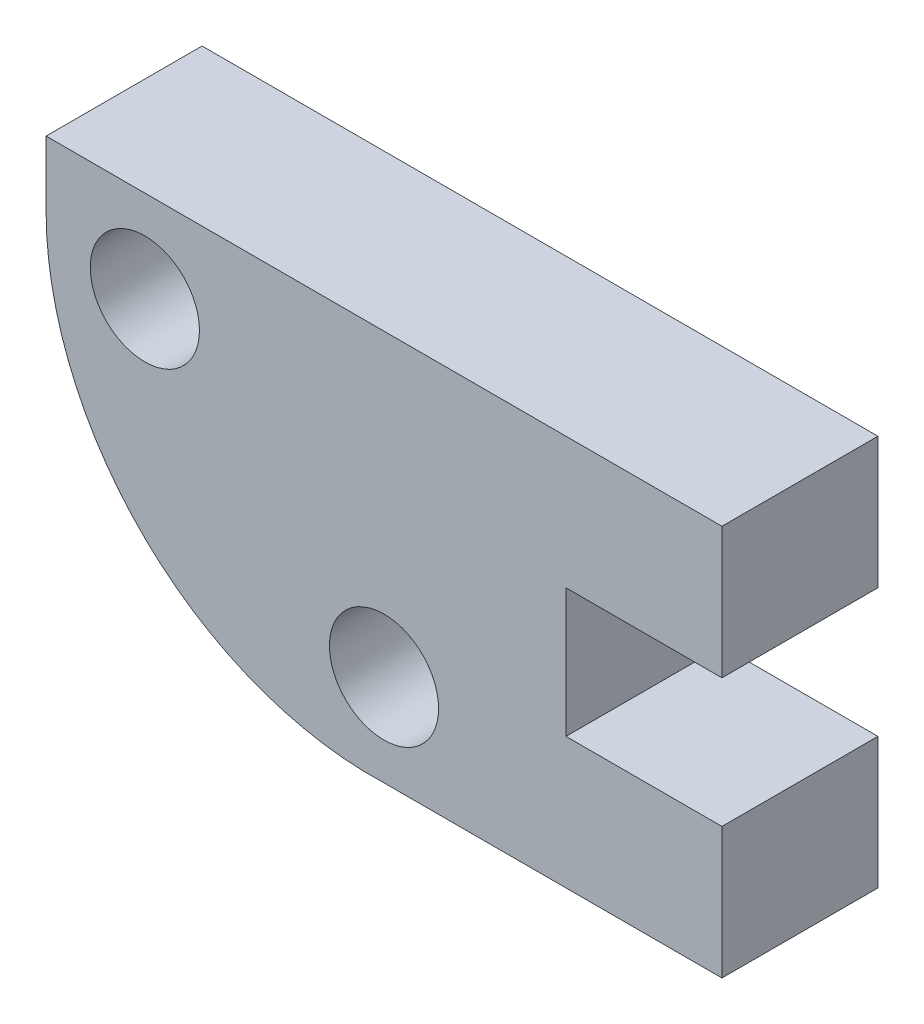
SolidWorks part; units mm, degrees
ref_plane "Plan de face" through (0, 0, 0) normal (0, 0, 1) x (1, 0, 0)
ref_plane "Plan de dessus" through (0, 0, 0) normal (0, 1, 0) x (1, 0, 0)
ref_plane "Plan de droite" through (0, 0, 0) normal (1, 0, 0) x (0, 0, -1)
sketch "Esquisse1" plane through (0, 0, 0) normal (0, 0, 1) x (1, 0, 0)
  line L0 (0, 0) -> (0, -5.05)
  line L1 (0, -5.05) -> (-6, -5.05)
  line L2 (-6, -5.05) -> (-6, -10)
  line L3 (-6, -10) -> (0, -10)
  line L4 (0, -10) -> (0, -15.05)
  line L5 (0, -15.05) -> (-13, -15.05)
  line L6 (-26, 0) -> (0, 0)
  line L7 (-22.2, -3.525) -> (-13, -3.525) construction
  line L8 (-13, -3.525) -> (-13, -11.525) construction
  line L9 (-22.2, -3.525) -> (-20.6153, -4.903) construction
  line L13 (-14.5847, -10.147) -> (-13, -11.525) construction
  line L14 (-26, 0) -> (-26, -2.5)
  circle A1 centre (-22.2, -3.525) radius 2.1
  circle A2 centre (-13, -11.525) radius 2.1
  arc A4 (-26, -2.5) -> (-13, -15.05) centre (-13.4422, -2.5) ccw
  dimension "D5" = 4.2
  dimension "D6" = 4.2
  dimension "D10" = 26
  dimension "D1" = 6
  dimension "D2" = 5.05
  dimension "D3" = 4.95
  dimension "D4" = 5.05
  dimension "D7" = 9.2
  dimension "D8" = 8
  dimension "D9" = 3.525
  dimension "D11" = 7
  dimension "D12" = 2.5
extrude "Boss.-Extru.1" add sketch "Esquisse1" along normal blind 6
